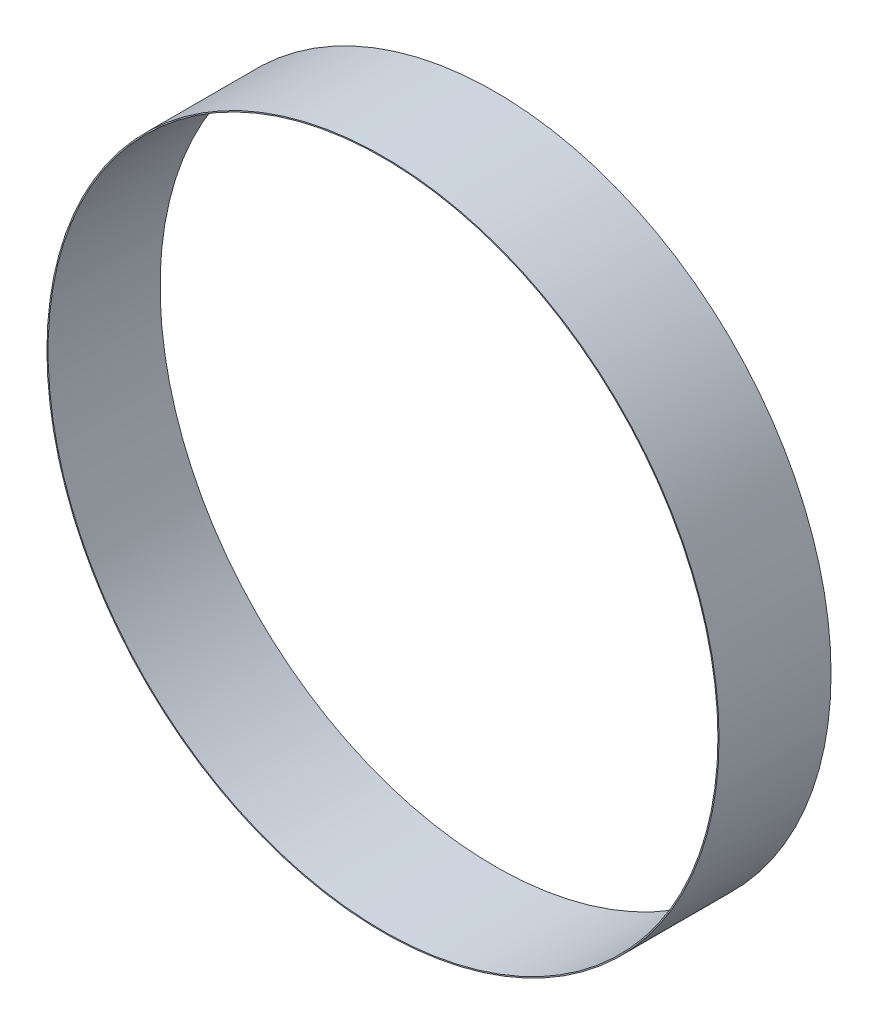
SolidWorks part; units mm, degrees
material "СТЕКЛОПЛАСТИК"
ref_plane "Спереди" through (0, 0, 0) normal (0, 0, 1) x (1, 0, 0)
ref_plane "Сверху" through (0, 0, 0) normal (0, 1, 0) x (1, 0, 0)
ref_plane "Справа" through (0, 0, 0) normal (1, 0, 0) x (0, 0, -1)
sketch "Эскиз1" plane through (0, 0, 0) normal (0, 0, 1) x (1, 0, 0)
  circle A0 centre (0, 0) radius 1495
  circle A1 centre (0, 0) radius 1500
  dimension "D1" = 3000
  dimension "D2" = 2990
extrude "Бобышка-Вытянуть1" add sketch "Эскиз1" along normal blind 500
